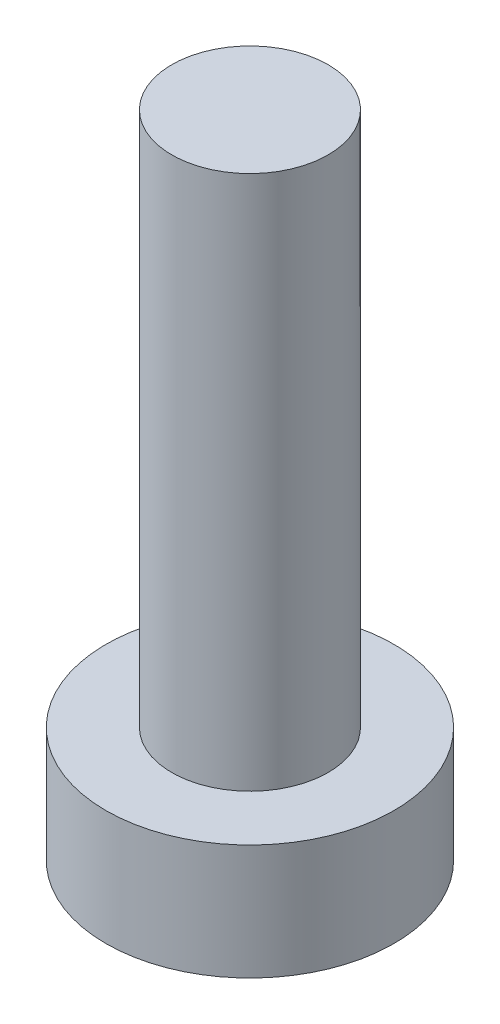
SolidWorks part; units mm, degrees
ref_plane "Front Plane" through (0, 0, 0) normal (0, 0, 1) x (1, 0, 0)
ref_plane "Top Plane" through (0, 0, 0) normal (0, 1, 0) x (1, 0, 0)
ref_plane "Right Plane" through (0, 0, 0) normal (1, 0, 0) x (0, 0, -1)
sketch "Sketch2" plane through (0, 0, 0) normal (0, 1, 0) x (1, 0, 0)
  circle A0 centre (0, 0) radius 3.5
  dimension "D1" = 7
extrude "Boss-Extrude1" add sketch "Sketch2" along normal blind 2.8
sketch "Sketch3" plane through (0, 2.8, 0) normal (0, 1, 0) x (1, 0, 0)
  circle A0 centre (0, 0) radius 1.9
  dimension "D1" = 3.8
extrude "Boss-Extrude2" add sketch "Sketch3" along normal blind 13
sketch "Sketch4" plane through (0, 0, 0) normal (0, -1, 0) x (1, 0, 0)
  line L1 (1.4434, 0) -> (0.7217, 1.25)
  line L2 (0.7217, 1.25) -> (-0.7217, 1.25)
  line L3 (-0.7217, 1.25) -> (-1.4434, 0)
  line L4 (-1.4434, 0) -> (-0.7217, -1.25)
  line L5 (-0.7217, -1.25) -> (0.7217, -1.25)
  line L6 (0.7217, -1.25) -> (1.4434, 0)
  circle A0 centre (0, 0) radius 1.25 construction
  dimension "D1" = 2.5
extrude "Cut-Extrude1" cut sketch "Sketch4" against normal blind 2.3
equation "\"Length\"=13"
equation "\"D1@Boss-Extrude2\"=\"Length\""
